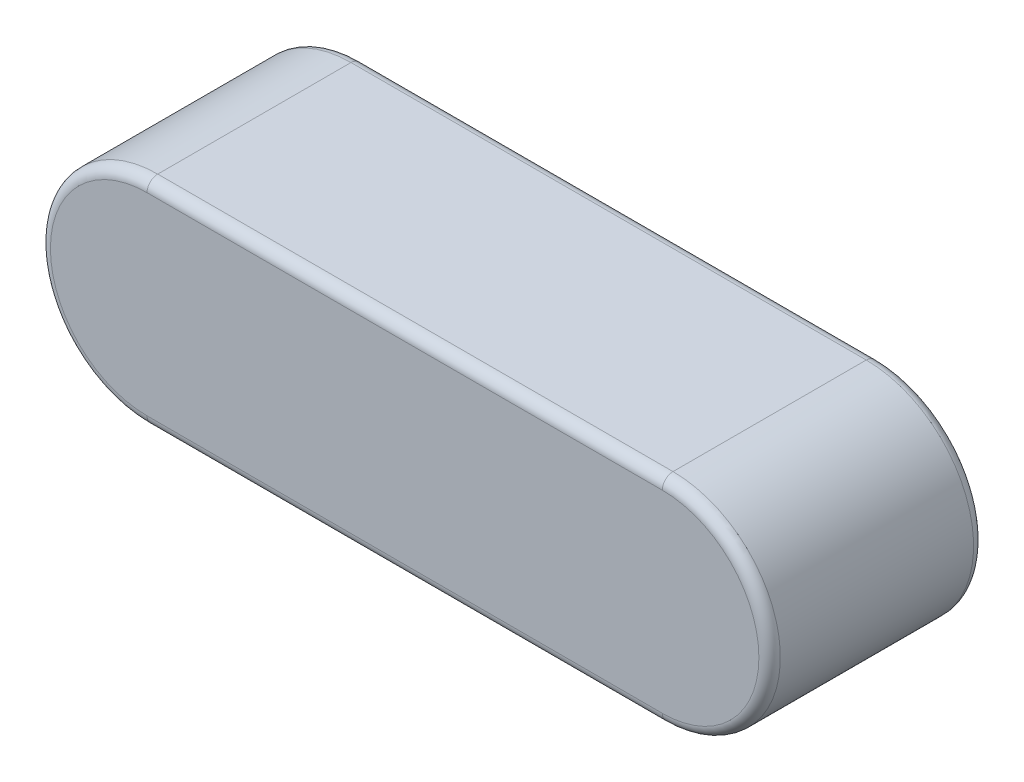
SolidWorks part; units mm, degrees
ref_plane "基准面1" through (0, 0, 0) normal (0, 0, 1) x (1, 0, 0)
ref_plane "基准面2" through (0, 0, 0) normal (0, 1, 0) x (1, 0, 0)
ref_plane "基准面3" through (0, 0, 0) normal (1, 0, 0) x (0, 0, -1)
sketch "尺寸草图" plane through (0, 0, 0) normal (0, 0, 1) x (1, 0, 0)
  line L0 (-9, 0) -> (9, 0) construction
  point P3 (-5, 0)
  point P4 (0, 0)
  point P5 (0.25, 0)
  point P8 (-5, 0)
  point P11 (0, 0)
  dimension "L" = 18
  dimension "b" = 5
  dimension "h" = 5
  dimension "r" = 0.25
sketch "草图1" plane through (0, 0, 0) normal (0, 0, 1) x (1, 0, 0)
  line L0 (-8.5, 0) -> (8.5, 0) construction
  line L1 (-6, 2.5) -> (6, 2.5)
  line L2 (-6, -2.5) -> (6, -2.5)
  line L3 (0, 2.9108) -> (0, -2.5) construction
  arc A0 (-6, 2.5) -> (-6, -2.5) centre (-6, 0) ccw
  arc A1 (6, 2.5) -> (6, -2.5) centre (6, 0) cw
  dimension "D3" = 17
  dimension "D1" = 2.5
extrude "基体-拉伸" add sketch "草图1" along normal blind 5
fillet "圆角1" radius 0.25 8 edges at (8.5, 0, 5) (0, 2.5, 5) (-8.5, 0, 5) (0, 2.5, 0) (8.5, 0, 0) (0, -2.5, 0) (-8.5, 0, 0) (0, -2.5, 5)
ref_plane "底部配合面6" through (0, 0, 0) normal (0, 0, -1) x (-1, 0, 0)
ref_plane "基准面7" through (0, 0, 0) normal (0, -1, 0) x (-1, 0, 0)
ref_plane "基准面8" through (-6, 0, 0) normal (-1, 0, 0) x (0, 0, -1)
ref_plane "配合基准面9" through (0, 0, 0) normal (-1, 0, 0) x (0, 0, -1)
